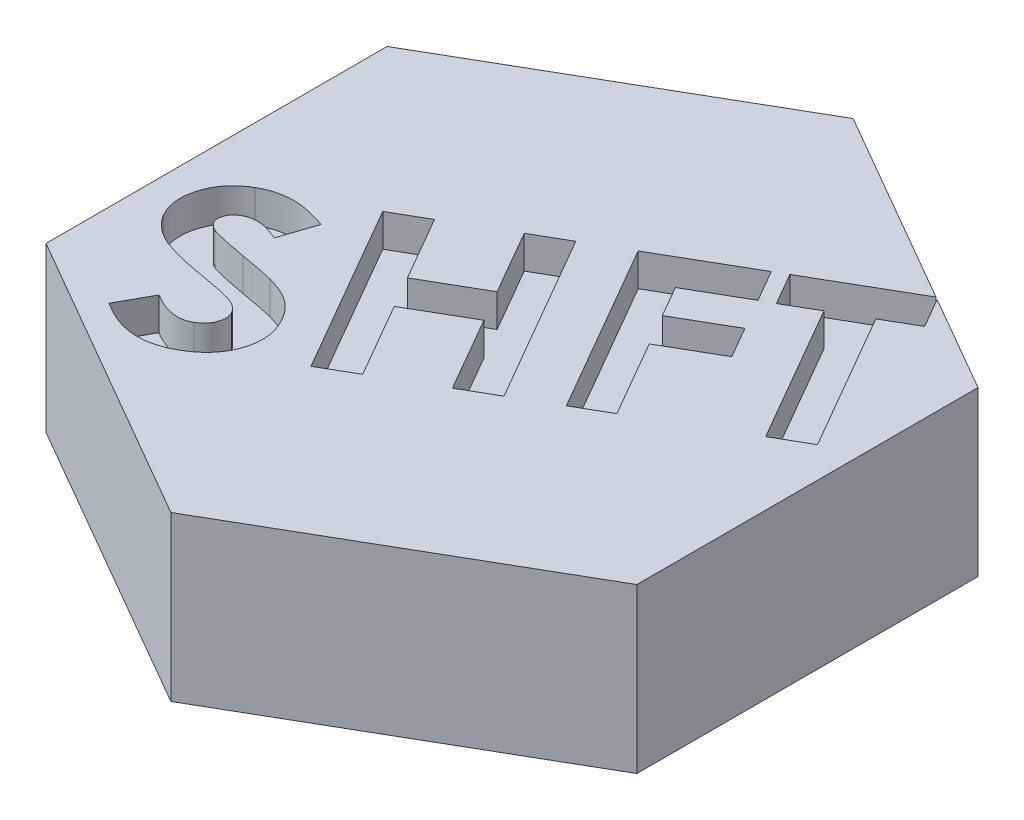
SolidWorks part; units mm, degrees
ref_plane "Plan de face" through (0, 0, 0) normal (0, 0, 1) x (1, 0, 0)
ref_plane "Plan de dessus" through (0, 0, 0) normal (0, 1, 0) x (1, 0, 0)
ref_plane "Plan de droite" through (0, 0, 0) normal (1, 0, 0) x (0, 0, -1)
sketch "Sketch1" plane through (0, 0, 0) normal (0, 1, 0) x (1, 0, 0)
  line L0 (0, 0) -> (9.025, 0) construction
  line L1 (9.025, 5.2106) -> (0, 10.4212)
  line L2 (0, 10.4212) -> (-9.025, 5.2106)
  line L3 (-9.025, 5.2106) -> (-9.025, -5.2106)
  line L4 (-9.025, -5.2106) -> (0, -10.4212)
  line L5 (0, -10.4212) -> (9.025, -5.2106)
  line L6 (9.025, -5.2106) -> (9.025, 5.2106)
  circle A0 centre (0, 0) radius 9.025 construction
  dimension "D1" = 18.05
extrude "Boss-Extrude1" add sketch "Sketch1" along normal blind 5
shell "Shell1" thickness 1
sketch "Sketch2" plane through (0, 4, 0) normal (0, -1, 0) x (1, 0, 0)
  line L6 (8.025, -4.6332) -> (8.025, 4.6332)
  line L7 (8.025, 4.6332) -> (0, 9.2665)
  line L8 (0, 9.2665) -> (-8.025, 4.6332)
  line L9 (-8.025, 4.6332) -> (-8.025, -4.6332)
  line L10 (-8.025, -4.6332) -> (0, -9.2665)
  line L11 (0, -9.2665) -> (8.025, -4.6332)
  line L12 (8.025, -4.6332) -> (8.025, 4.6332)
  line L13 (8.025, 4.6332) -> (0, 9.2665)
  line L14 (0, 9.2665) -> (-8.025, 4.6332)
  line L15 (-8.025, 4.6332) -> (-8.025, -4.6332)
  line L16 (-8.025, -4.6332) -> (0, -9.2665)
  line L17 (0, -9.2665) -> (8.025, -4.6332)
  dimension "D1" = 0
extrude "Boss-Extrude2" add sketch "Sketch2" along normal blind 2
sketch "Sketch3" plane through (0, 2, 0) normal (0, -1, 0) x (1, 0, 0)
  line L1 (-3.4, -2.45) -> (3.4, -2.45)
  line L2 (-3.4, -2.45) -> (-3.4, 2.45)
  line L3 (-3.4, 2.45) -> (3.4, 2.45)
  line L4 (3.4, -2.45) -> (3.4, 2.45)
  line L5 (-3.4, -2.45) -> (3.4, 2.45) construction
  line L6 (-3.4, 2.45) -> (3.4, -2.45) construction
  point P0 (0, 0)
  dimension "D1" = 4.9
  dimension "D2" = 6.8
extrude "Boss-Extrude3" add sketch "Sketch3" along normal blind 3.5
sketch "Sketch4" plane through (0, -1.5, 0) normal (0, -1, 0) x (1, 0, 0)
  line L0 (0, -2.1) -> (0, 2.1) construction
  line L1 (2.1, 0) -> (-2.1, 0) construction
  line L2 (2.1, -0.65) -> (2.1, 0.65)
  line L3 (-0.75, 2.1) -> (0.75, 2.1)
  line L4 (0.75, 2.1) -> (0.75, 0.65)
  line L5 (0.75, 0.65) -> (2.1, 0.65)
  line L6 (-0.75, -2.1) -> (0.75, -2.1)
  line L7 (0.75, -2.1) -> (0.75, -0.65)
  line L8 (0.75, -0.65) -> (2.1, -0.65)
  line L9 (-0.75, -2.1) -> (-0.75, -0.65)
  line L10 (-0.75, -0.65) -> (-2.1, -0.65)
  line L11 (-2.1, -0.65) -> (-2.1, 0.65)
  line L12 (-2.1, 0.65) -> (-0.75, 0.65)
  line L13 (-0.75, 0.65) -> (-0.75, 2.1)
  dimension "D1" = 1.5
  dimension "D2" = 1.3
  dimension "D3" = 4.2
extrude "Cut-Extrude1" cut sketch "Sketch4" against normal blind 3.5
sketch "Sketch5" plane through (0, 5, 0) normal (0, 1, 0) x (1, 0, 0)
  line L0 (-6.0651, -6.9195) -> (9.025, 1.7927) construction
  line L1 (-9.025, -5.2106) -> (0, -10.4212) construction
  line L2 (9.025, -5.2106) -> (9.025, 5.2106) construction
  line L3 (0, -10.4212) -> (9.025, -5.2106) construction
  text T0 "SHFT" font "Century Gothic" height 6
  point P8 (0, 0)
  point P10 (9.025, 1.3422)
  point P11 (0, 0)
  point P12 (0, 0)
  point P13 (0, 0)
  point P14 (9.025, 1.7927)
extrude "Cut-Extrude2" cut sketch "Sketch5" against normal blind 1
equation "\"s\"= 18.05mm"
equation "\"witvnsdfklgvj_thickness\"= 5mm"
equation "\"D1@Sketch1\"=\"s\""
equation "\"D1@Boss-Extrude1\"=\"witvnsdfklgvj_thickness\""
equation "\"cross_thickness\"= 3.5mm"
equation "\"D1@Boss-Extrude3\"=\"cross_thickness\""
equation "\"D1@Cut-Extrude1\"=\"cross_thickness\""
